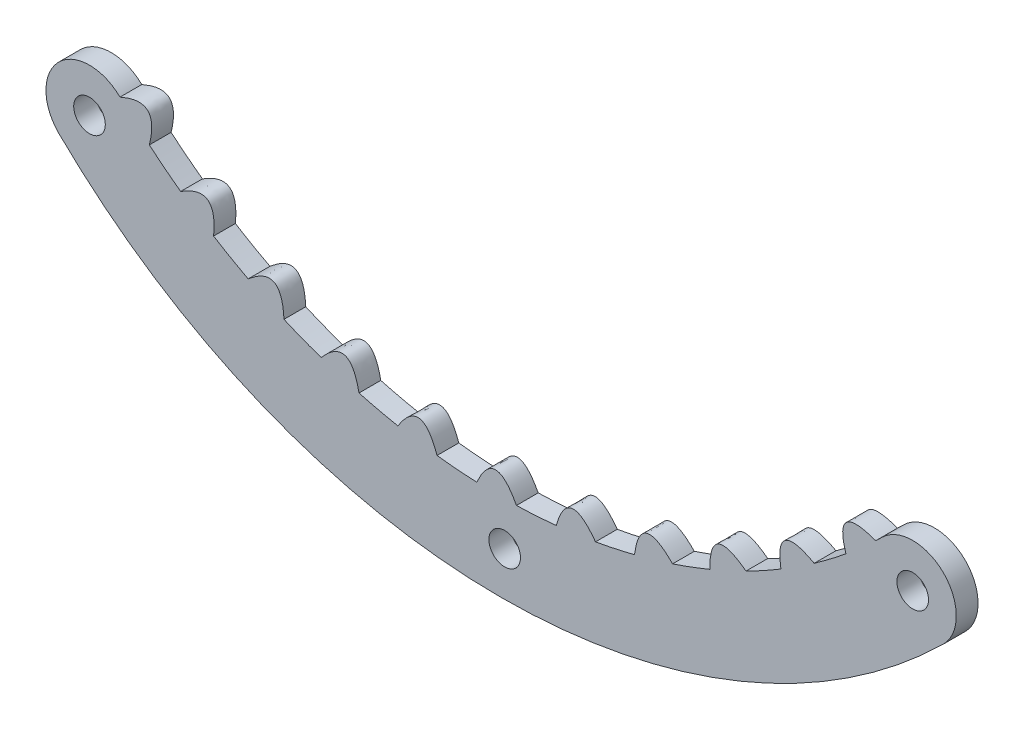
SolidWorks part; units mm, degrees
ref_plane "前视基准面" through (0, 0, 0) normal (0, 0, 1) x (1, 0, 0)
ref_plane "上视基准面" through (0, 0, 0) normal (0, 1, 0) x (1, 0, 0)
ref_plane "右视基准面" through (0, 0, 0) normal (1, 0, 0) x (0, 0, -1)
other "Configuration Table"
sketch "草图1" plane through (0, 0, 0) normal (0, 0, 1) x (1, 0, 0)
  line L0 (0, 0) -> (0, -35.7077) construction
  line L1 (-34.9994, -35.7077) -> (34.9994, -35.7077)
  line L2 (0, 0) -> (-34.9994, -35.7077)
  line L3 (-34.9994, -35.7077) -> (-40.5993, -41.421) construction
  line L4 (0, 0) -> (34.9994, -35.7077)
  line L5 (34.9994, -35.7077) -> (40.5993, -41.421) construction
  circle A0 centre (0, 0) radius 50
  circle A1 centre (0, 0) radius 58
  arc A2 (-34.9994, -35.7077) -> (-40.5993, -41.421) centre (-37.7994, -38.5643) ccw
  arc A3 (34.9994, -35.7077) -> (40.5993, -41.421) centre (37.7994, -38.5643) cw
  point P7 (0, -35.7077)
  dimension "D1" = 100
  dimension "D2" = 116
extrude "凸台-拉伸1" add sketch "草图1" along normal blind 2
sketch "草图2" plane through (0, 0, 2) normal (0, 0, 1) x (1, 0, 0)
  arc A3 (-34.9994, -35.7077) -> (34.9994, -35.7077) centre (0, 0) ccw construction
  arc A4 (-34.9994, -35.7077) -> (35.0319, -35.6758) centre (0, 0) ccw
  spline S0 degree 2 poles (-34.9994, -35.7077) (-31.293, -34.0515) (-32.3048, -38.1628) knots 0 0 0 1 1 1
  spline S33 degree 2 poles (31.6656, -38.6948) (30.4246, -34.8296) (34.4007, -36.2849) knots 0 0 0 1 1 1
  spline S34 degree 2 poles (25.6941, -42.893) (25.0292, -38.8883) (28.751, -40.907) knots 0 0 0 1 1 1
  spline S35 degree 2 poles (19.175, -46.177) (19.1003, -42.1181) (22.4885, -44.6572) knots 0 0 0 1 1 1
  spline S36 degree 2 poles (12.2473, -48.4768) (12.7643, -44.4503) (15.7467, -47.4557) knots 0 0 0 1 1 1
  spline S37 degree 2 poles (5.0585, -49.7435) (6.1563, -45.8351) (8.6693, -49.2427) knots 0 0 0 1 1 1
  spline S38 degree 2 poles (-2.2381, -49.9499) (-0.583, -46.243) (1.4071, -49.9802) knots 0 0 0 1 1 1
  spline S39 degree 2 poles (-9.487, -49.0917) (-7.3098, -45.6653) (-5.8851, -49.6524) knots 0 0 0 1 1 1
  spline S40 degree 2 poles (-16.5338, -47.1872) (-13.8809, -44.1144) (-13.0518, -48.2664) knots 0 0 0 1 1 1
  spline S41 degree 2 poles (-23.2281, -44.277) (-20.156, -41.6232) (-19.9404, -45.8517) knots 0 0 0 1 1 1
  spline S42 degree 2 poles (-29.4273, -40.4232) (-26.0016, -38.2449) (-26.404, -42.4598) knots 0 0 0 1 1 1
extrude "凸台-拉伸6" add sketch "草图2" against normal blind 2 contours S0 A4 | S42 A4 | S41 A4 | S40 A4 | S39 A4 | S38 A4 | S37 A4 | S33 A4 | S34 A4 | S35 A4 | S36 A4
sketch "草图3" plane through (0, 0, 2) normal (0, 0, 1) x (1, 0, 0)
  arc A0 (-34.9994, -35.7077) -> (-40.5993, -41.421) centre (-37.7994, -38.5643) ccw construction
  arc A1 (-34.9994, -35.7077) -> (-40.5993, -41.421) centre (-37.7994, -38.5643) ccw
  circle A2 centre (-37.7994, -38.5643) radius 1.45
  arc A3 (40.5993, -41.421) -> (34.9994, -35.7077) centre (37.7994, -38.5643) ccw construction
  arc A4 (40.5993, -41.421) -> (34.9994, -35.7077) centre (37.7994, -38.5643) ccw
  circle A5 centre (37.7994, -38.5643) radius 1.45
  circle A6 centre (0.3289, -53.9565) radius 1.45
  point P10 (0, 0)
  dimension "D1" = 2.9
  dimension "D2" = 2.9
  dimension "D3" = 2.9
extrude "切除-拉伸1" cut sketch "草图3" against normal blind 2 contours A2 | A6 | A5
